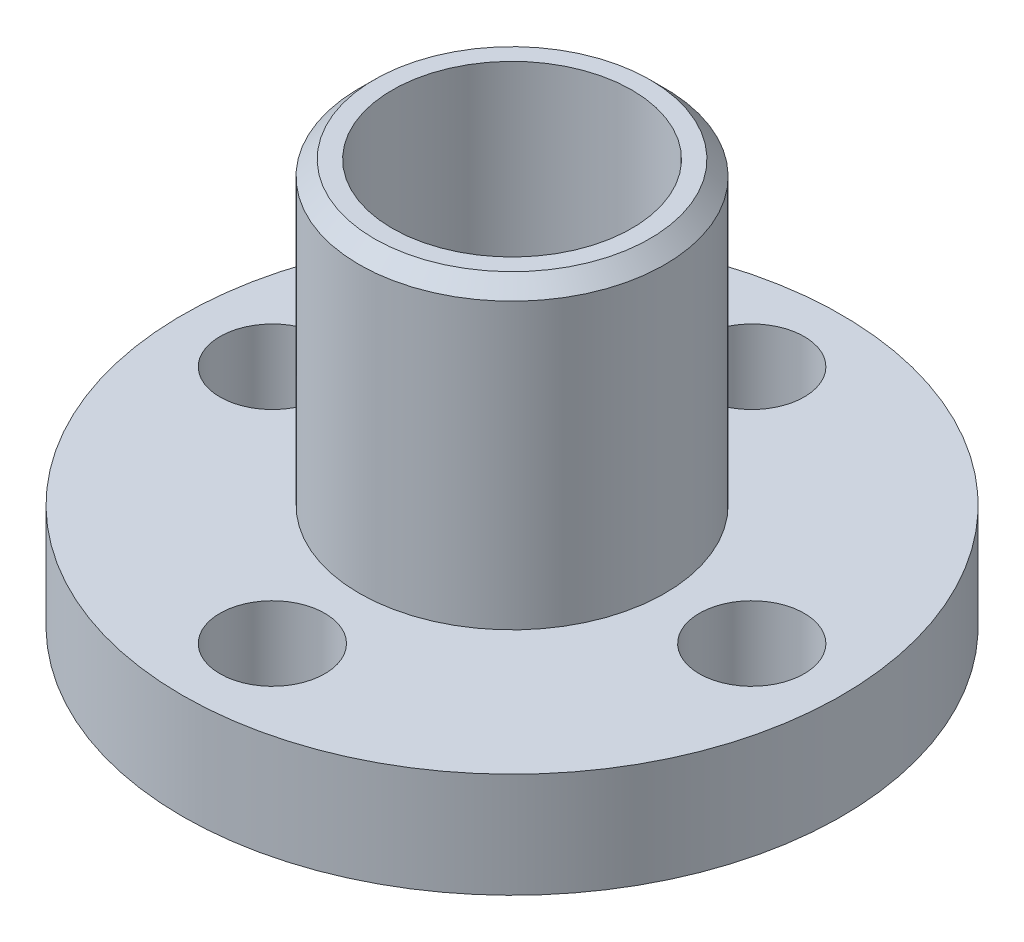
SolidWorks part; units mm, degrees
ref_plane "前视基准面" through (0, 0, 0) normal (0, 0, 1) x (1, 0, 0)
ref_plane "上视基准面" through (0, 0, 0) normal (0, 1, 0) x (1, 0, 0)
ref_plane "右视基准面" through (0, 0, 0) normal (1, 0, 0) x (0, 0, -1)
sketch "草图1" plane through (0, 0, 0) normal (0, 1, 0) x (1, 0, 0)
  circle A0 centre (0, 0) radius 11
  dimension "D1" = 22
extrude "凸台-拉伸1" add sketch "草图1" along normal blind 3.5 contours A0
sketch "草图2" plane through (0, 3.5, 0) normal (0, 1, 0) x (1, 0, 0)
  circle A0 centre (0, 0) radius 4
  dimension "D1" = 8
extrude "切除-拉伸1" cut sketch "草图2" against normal through all
sketch "草图3" plane through (0, 3.5, 0) normal (0, 1, 0) x (1, 0, 0)
  circle A0 centre (0, 0) radius 5.1
  circle A1 centre (0, 0) radius 4
  dimension "D1" = 10.2
extrude "凸台-拉伸2" add sketch "草图3" along normal blind 10
sketch "草图6" plane through (0, 0, 0) normal (0, -1, 0) x (1, 0, 0)
  circle A0 centre (0, 0) radius 5.1
  circle A1 centre (0, 0) radius 4
  dimension "D1" = 10.2
extrude "凸台-拉伸3" add sketch "草图6" along normal blind 1.5
sketch "草图7" plane through (0, 3.5, 0) normal (0, 1, 0) x (1, 0, 0)
  line L0 (0, 0) -> (0, 11) construction
  circle A0 centre (0, 0) radius 11 construction
  circle A1 centre (0, 8) radius 1.75
  circle A2 centre (8, 0) radius 1.75
  circle A3 centre (0, -8) radius 1.75
  circle A4 centre (-8, 0) radius 1.75
  point P17 (0, 0)
  dimension "D1" = 3.5
  dimension "D2" = 8
  dimension "D3" = 4
extrude "切除-拉伸2" cut sketch "草图7" against normal through all
chamfer "倒角1" distance 0.5 angle 45 2 edges at (0, 13.5, 5.1) (0, -1.5, -5.1)
